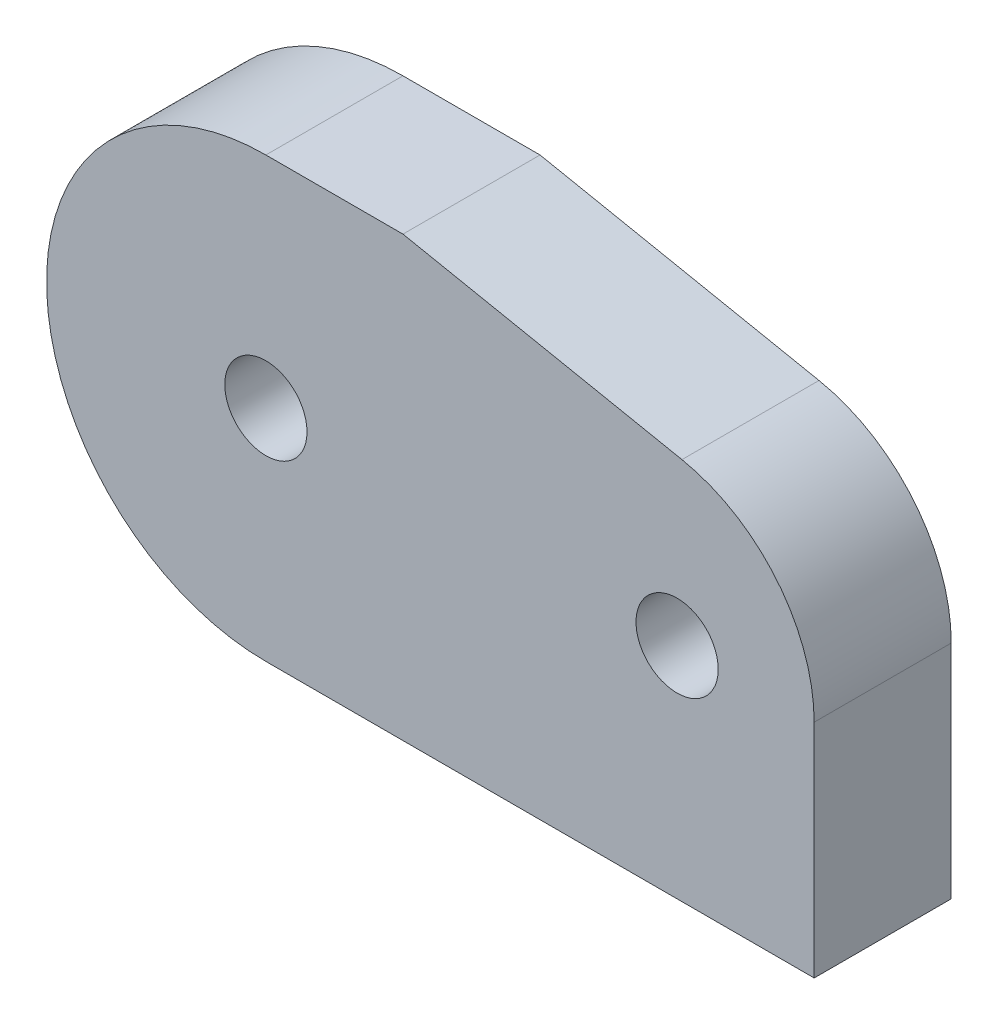
SolidWorks part; units mm, degrees
ref_plane "Plan de face" through (0, 0, 0) normal (0, 0, 1) x (1, 0, 0)
ref_plane "Plan de dessus" through (0, 0, 0) normal (0, 1, 0) x (1, 0, 0)
ref_plane "Plan de droite" through (0, 0, 0) normal (1, 0, 0) x (0, 0, -1)
sketch "Esquisse1" plane through (0, 0, 0) normal (0, 0, 1) x (1, 0, 0)
  line L0 (0, 0) -> (80, 0) construction
  line L1 (20, 0) -> (20, 23.8674) construction
  line L2 (0, 0) -> (0, 35) construction
  line L3 (0, 35) -> (55, 35) construction
  line L4 (0, 8) -> (5, 8)
  line L5 (82.6316, 13.5175) -> (85, 11.6762) construction
  line L6 (20, 8) -> (32.7289, 8) construction
  line L7 (0, -8) -> (55, -8) construction
  line L8 (55, 35) -> (55, -8) construction
  line L9 (0, -8) -> (20, -8)
  line L10 (20, -8) -> (20, 5)
  line L11 (20, 5) -> (5, 8)
  circle A0 centre (0, 0) radius 1.5
  arc A1 (0, 8) -> (0, -8) centre (0, 0) ccw
  circle A2 centre (55, 35) radius 35 construction
  arc A3 (32.7289, 8) -> (82.6316, 13.5175) centre (55, 35) ccw construction
  arc A4 (82.6316, 13.5175) -> (87.5479, 10.0925) centre (85, 11.6762) cw construction
  arc A5 (55, -8) -> (87.5479, 10.0925) centre (55, 30.3227) ccw construction
  circle A6 centre (15, 0) radius 1.5
  dimension "D3" = 3
  dimension "D4" = 35
  dimension "D6" = 70
  dimension "D7" = 3
  dimension "D8" = 8
  dimension "D9" = 30
  dimension "D10" = 15
  dimension "D14" = 3
  dimension "D1" = 20
  dimension "D2" = 80
  dimension "D5" = 55
  dimension "D11" = 13
  dimension "D12" = 15
  dimension "D13" = 20
extrude "Boss.-Extru.1" add sketch "Esquisse1" along normal blind 5
fillet "Congé1" radius 6 1 edges at (20, 5, 2.5)
